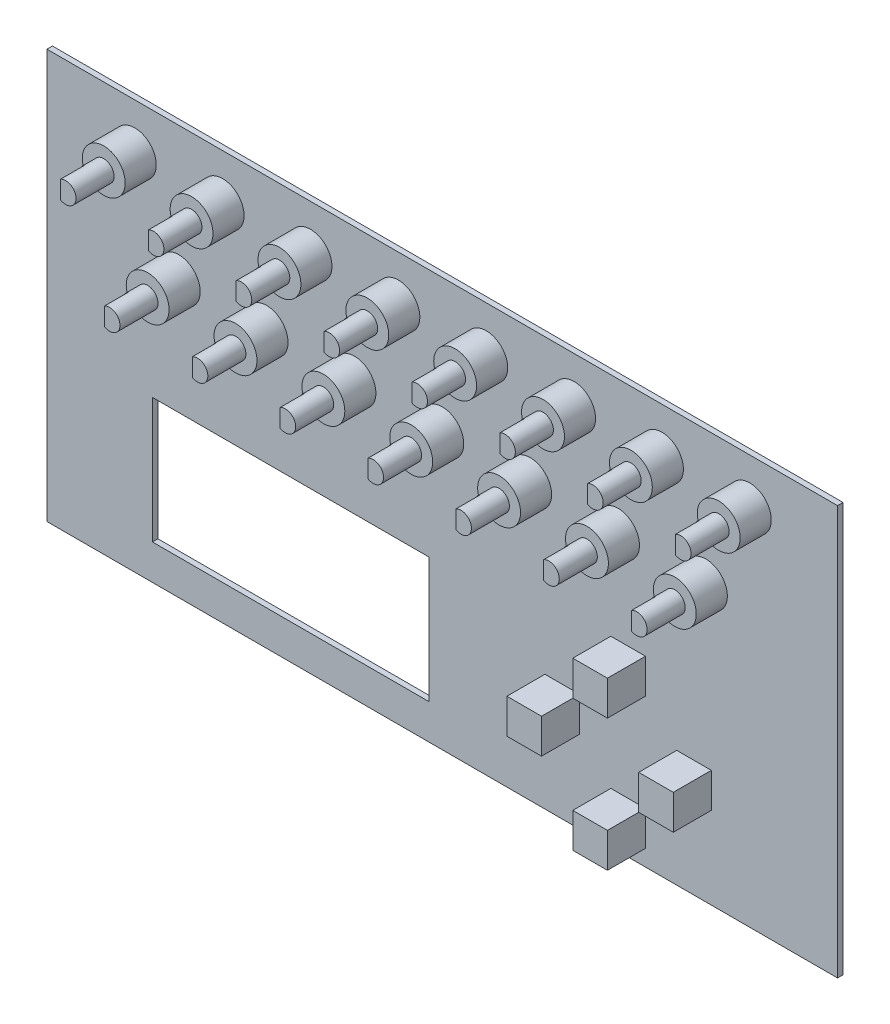
SolidWorks part; units mm, degrees
ref_plane "Front Plane" through (0, 0, 0) normal (0, 0, 1) x (1, 0, 0)
ref_plane "Top Plane" through (0, 0, 0) normal (0, 1, 0) x (1, 0, 0)
ref_plane "Right Plane" through (0, 0, 0) normal (1, 0, 0) x (0, 0, -1)
sketch "Model" plane through (0, 0, 0) normal (0, 0, 1) x (1, 0, 0)
  line L0 (181.071, 10.5156) -> (181.071, 22.2504)
  line L1 (181.198, 22.3774) -> (192.9328, 22.3774)
  line L2 (193.0598, 22.2504) -> (193.0598, 10.5156)
  line L3 (192.9328, 10.3886) -> (181.198, 10.3886)
  line L4 (154.8328, 10.3886) -> (143.098, 10.3886)
  line L5 (142.971, 10.5156) -> (142.971, 22.2504)
  line L6 (143.098, 22.3774) -> (154.8328, 22.3774)
  line L7 (154.9598, 22.2504) -> (154.9598, 10.5156)
  line L8 (173.8828, -8.6614) -> (162.148, -8.6614)
  line L9 (162.021, -8.5344) -> (162.021, 3.2004)
  line L10 (162.148, 3.3274) -> (173.8828, 3.3274)
  line L11 (174.0098, 3.2004) -> (174.0098, -8.5344)
  line L12 (173.8828, 29.4386) -> (162.148, 29.4386)
  line L13 (162.021, 29.5656) -> (162.021, 41.3004)
  line L14 (162.148, 41.4274) -> (173.8828, 41.4274)
  line L15 (174.0098, 41.3004) -> (174.0098, 29.5656)
  line L16 (185.2461, -6.7752) -> (195.8125, -6.7752)
  line L17 (195.8125, -6.7752) -> (195.8125, 3.3848)
  line L18 (195.8125, 3.3848) -> (185.2461, 3.3848)
  line L19 (185.2461, 3.3848) -> (185.2461, -6.7752)
  line L20 (1.8956, -0.1228) -> (1.8956, -10.6892)
  line L21 (1.8956, -10.6892) -> (14.5956, -10.6892)
  line L22 (14.5956, -10.6892) -> (14.5956, -0.1228)
  line L23 (14.5956, -0.1228) -> (1.8956, -0.1228)
  line L24 (112.1837, -0.2785) -> (112.1837, -10.8449)
  line L25 (112.1837, -10.8449) -> (124.8837, -10.8449)
  line L26 (124.8837, -10.8449) -> (124.8837, -0.2785)
  line L27 (124.8837, -0.2785) -> (112.1837, -0.2785)
  line L28 (127.7722, -0.2785) -> (127.7722, -10.8449)
  line L29 (127.7722, -10.8449) -> (140.4722, -10.8449)
  line L30 (140.4722, -10.8449) -> (140.4722, -0.2785)
  line L31 (140.4722, -0.2785) -> (127.7722, -0.2785)
  line L32 (16.003, 0.0332) -> (16.003, -10.5332)
  line L33 (16.003, -10.5332) -> (28.703, -10.5332)
  line L34 (28.703, -10.5332) -> (28.703, 0.0332)
  line L35 (28.703, 0.0332) -> (16.003, 0.0332)
  line L82 (0, -12.3612) -> (0, 105.9089)
  line L83 (0, 105.9089) -> (228.5525, 105.9089)
  line L84 (228.5525, 105.9089) -> (228.5525, -12.3612)
  line L85 (228.5525, -12.3612) -> (0, -12.3612)
  line L86 (30.48, -2.2225) -> (30.48, 33.9725)
  line L87 (30.48, 33.9725) -> (110.49, 33.9725)
  line L88 (110.49, 33.9725) -> (110.49, -2.2225)
  line L89 (110.49, -2.2225) -> (30.48, -2.2225)
  arc A0 (181.198, 22.3774) -> (181.071, 22.2504) centre (181.198, 22.2504) ccw
  arc A1 (193.0598, 22.2504) -> (192.9328, 22.3774) centre (192.9328, 22.2504) ccw
  arc A2 (192.9328, 10.3886) -> (193.0598, 10.5156) centre (192.9328, 10.5156) ccw
  arc A3 (181.071, 10.5156) -> (181.198, 10.3886) centre (181.198, 10.5156) ccw
  arc A15 (142.971, 10.5156) -> (143.098, 10.3886) centre (143.098, 10.5156) ccw
  arc A16 (143.098, 22.3774) -> (142.971, 22.2504) centre (143.098, 22.2504) ccw
  arc A17 (154.9598, 22.2504) -> (154.8328, 22.3774) centre (154.8328, 22.2504) ccw
  arc A18 (154.8328, 10.3886) -> (154.9598, 10.5156) centre (154.8328, 10.5156) ccw
  arc A22 (162.021, -8.5344) -> (162.148, -8.6614) centre (162.148, -8.5344) ccw
  arc A23 (162.148, 3.3274) -> (162.021, 3.2004) centre (162.148, 3.2004) ccw
  arc A24 (174.0098, 3.2004) -> (173.8828, 3.3274) centre (173.8828, 3.2004) ccw
  arc A25 (173.8828, -8.6614) -> (174.0098, -8.5344) centre (173.8828, -8.5344) ccw
  arc A29 (162.021, 29.5656) -> (162.148, 29.4386) centre (162.148, 29.5656) ccw
  arc A30 (162.148, 41.4274) -> (162.021, 41.3004) centre (162.148, 41.3004) ccw
  arc A31 (174.0098, 41.3004) -> (173.8828, 41.4274) centre (173.8828, 41.3004) ccw
  arc A32 (173.8828, 29.4386) -> (174.0098, 29.5656) centre (173.8828, 29.5656) ccw
  circle A36 centre (25.4, 92.71) radius 6.731
  circle A37 centre (50.8, 92.71) radius 6.731
  circle A38 centre (76.2, 92.71) radius 6.731
  circle A39 centre (101.6, 92.71) radius 6.731
  circle A40 centre (127, 92.71) radius 6.731
  circle A41 centre (152.4, 92.71) radius 6.731
  circle A42 centre (177.8, 92.71) radius 6.731
  circle A43 centre (203.2, 92.71) radius 6.731
  circle A44 centre (190.5, 67.31) radius 6.731
  circle A45 centre (38.1, 67.31) radius 6.731
  circle A46 centre (63.5, 67.31) radius 6.731
  circle A47 centre (88.9, 67.31) radius 6.731
  circle A48 centre (114.3, 67.31) radius 6.731
  circle A49 centre (139.7, 67.31) radius 6.731
  circle A50 centre (165.1, 67.31) radius 6.731
extrude "Boss-Extrude3" add sketch "Model" along normal blind 1.5875 contours L83 L84 L85 L82 | L87 L88 L89 L86
sketch "Sketch4" plane through (0, 0, 1.5875) normal (0, 0, 1) x (1, 0, 0)
  circle A0 centre (25.4, 92.71) radius 6.1976
  dimension "D1" = 12.3952
extrude "Boss-Extrude4" add sketch "Sketch4" along normal blind 8.9916
pattern_linear "LPattern1" count 15 spacing 12.7 along (1, 0, 0) count 2 spacing 25.4 along (0, -1, 0) skipping (0, 1), (1, 0), (2, 1), (3, 0), (4, 1), (5, 0), (6, 1), (7, 0), (8, 1), (9, 0), (10, 1), (11, 0), (12, 1), (13, 0), (14, 1) of "Boss-Extrude4"
sketch "Sketch5" plane through (0, 0, 10.5791) normal (0, 0, 1) x (1, 0, 0)
  circle A0 centre (25.4, 92.71) radius 2.9972
  dimension "D1" = 5.9944
extrude "Boss-Extrude5" add sketch "Sketch5" along normal blind 10.9982
sketch "Sketch8" plane through (0, 0, 21.5773) normal (0, 0, 1) x (1, 0, 0)
  line L1 (23.9014, 96.3727) -> (21.4543, 96.3727)
  line L2 (23.9014, 96.3727) -> (23.9014, 88.7299)
  line L3 (23.9014, 88.7299) -> (21.4543, 88.7299)
  line L4 (21.4543, 96.3727) -> (21.4543, 88.7299)
  dimension "D1" = 1.4986
extrude "Cut-Extrude1" cut sketch "Sketch8" against normal blind 7.0104
pattern_linear "LPattern2" count 15 spacing 12.7 along (1, 0, 0) count 2 spacing 25.4 along (0, -1, 0) skipping (0, 1), (1, 0), (2, 1), (3, 0), (4, 1), (5, 0), (6, 1), (7, 0), (8, 1), (9, 0), (10, 1), (11, 0), (12, 1), (13, 0), (14, 1) of "Cut-Extrude1", "Boss-Extrude5"
sketch "Sketch6" plane through (0, 0, 1.5875) normal (0, 0, 1) x (1, 0, 0)
  line L14 (153.9692, 21.3868) -> (143.9616, 21.3868)
  line L15 (153.9692, 11.3792) -> (153.9692, 21.3868)
  line L16 (143.9616, 11.3792) -> (153.9692, 11.3792)
  line L17 (143.9616, 21.3868) -> (143.9616, 11.3792)
  line L18 (153.9692, 21.3868) -> (143.9616, 21.3868)
  line L19 (153.9692, 11.3792) -> (153.9692, 21.3868)
  line L20 (143.9616, 11.3792) -> (153.9692, 11.3792)
  line L21 (143.9616, 21.3868) -> (143.9616, 11.3792)
  dimension "D1" = 0.9906
extrude "Boss-Extrude6" add sketch "Sketch6" along normal blind 10.9982
pattern_linear "LPattern3" count 3 spacing 19.05 along (1, 0, 0) count 2 spacing 19.05 along (0, -1, 0) skipping (0, 1), (1, 0), (2, 1) of "Boss-Extrude6"
pattern_linear "LPattern4" count 2 spacing 19.05 along (0, 1, 0) count 2 spacing 19.05 along (1, 0, 0) skipping (0, 1), (1, 0) of "Boss-Extrude6"
